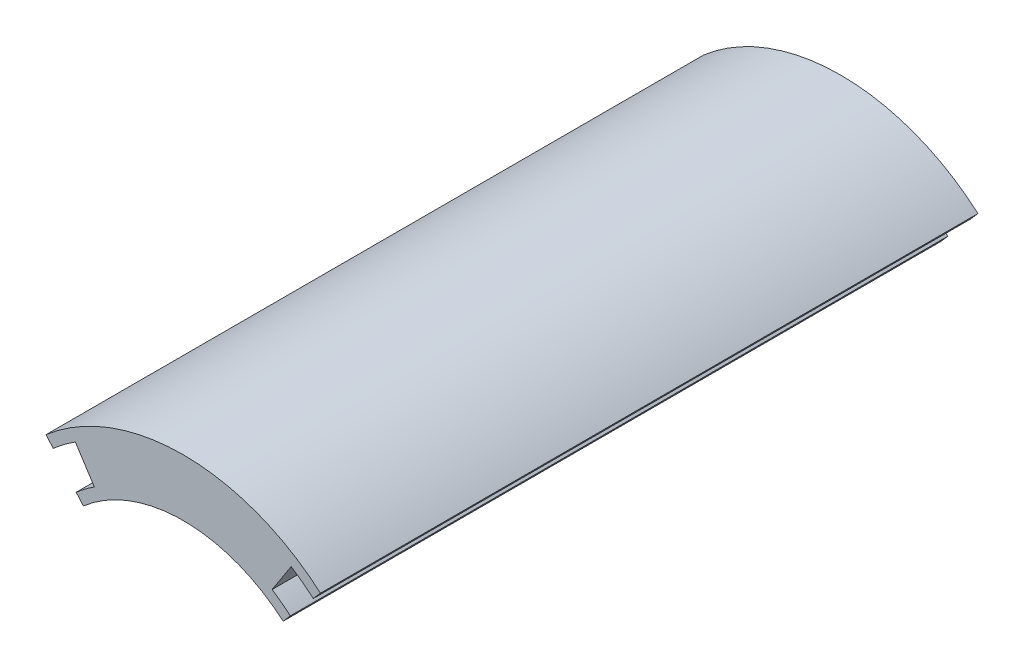
SolidWorks part; units mm, degrees
ref_plane "Front Plane" through (0, 0, 0) normal (0, 0, 1) x (1, 0, 0)
ref_plane "Top Plane" through (0, 0, 0) normal (0, 1, 0) x (1, 0, 0)
ref_plane "Right Plane" through (0, 0, 0) normal (1, 0, 0) x (0, 0, -1)
sketch "Sketch1" plane through (0, 0, 0) normal (0, 0, 1) x (1, 0, 0)
  line L0 (0, 0) -> (-12.5232, 14.4215) construction
  line L1 (0, 0) -> (12.5232, 14.4215) construction
  line L2 (0, 0) -> (-10.3942, 16.0241) construction
  line L3 (0, 0) -> (10.3942, 16.0241) construction
  line L4 (-12.5232, 14.4215) -> (-11.8675, 13.6665)
  line L5 (-9.7694, 11.2503) -> (-9.1137, 10.4952)
  line L6 (12.5232, 14.4215) -> (11.8675, 13.6665)
  line L7 (9.7694, 11.2503) -> (9.1137, 10.4952)
  line L8 (9.85, 15.1851) -> (8.1086, 12.5004)
  line L9 (-9.85, 15.1851) -> (-8.1086, 12.5004)
  line L10 (-9.85, 15.1851) -> (9.85, 15.1851) construction
  line L11 (9.1137, 10.4952) -> (-9.1137, 10.4952) construction
  arc A0 (-12.5232, 14.4215) -> (12.5232, 14.4215) centre (0, 0) cw
  arc A1 (-9.1137, 10.4952) -> (9.1137, 10.4952) centre (0, 0) cw
  arc A2 (-11.8675, 13.6665) -> (-9.85, 15.1851) centre (0, 0) cw
  arc A3 (-9.7694, 11.2503) -> (-8.1086, 12.5004) centre (0, 0) cw
  arc A4 (9.85, 15.1851) -> (11.8675, 13.6665) centre (0, 0) cw
  arc A5 (8.1086, 12.5004) -> (9.7694, 11.2503) centre (0, 0) cw
  dimension "D1" = 18.1
  dimension "D2" = 14.9
  dimension "D3" = 1
  dimension "D4" = 1
  dimension "D5" = 19.7
  dimension "D6" = 8
extrude "Boss-Extrude1" add sketch "Sketch1" along normal blind 60
